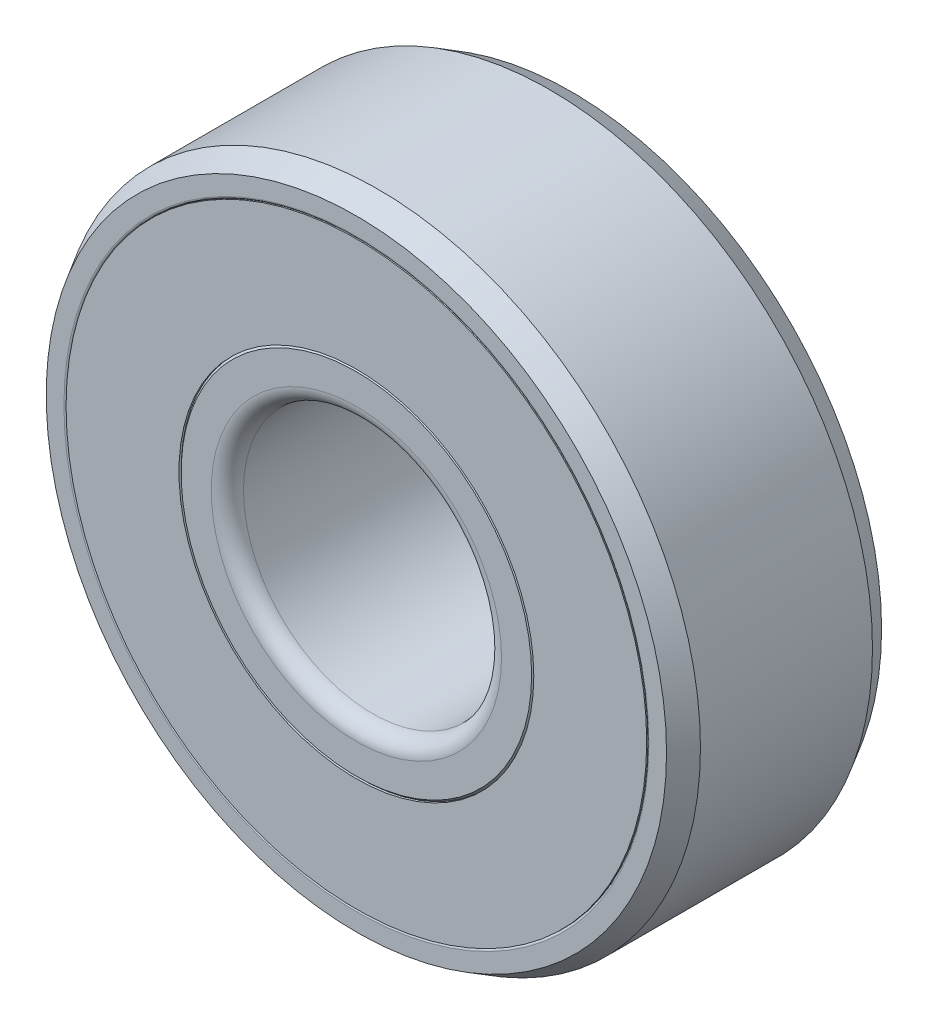
SolidWorks part; units mm, degrees
ref_plane "Front Plane" through (0, 0, 0) normal (0, 0, 1) x (1, 0, 0)
ref_plane "Top Plane" through (0, 0, 0) normal (0, 1, 0) x (1, 0, 0)
ref_plane "Right Plane" through (0, 0, 0) normal (1, 0, 0) x (0, 0, -1)
sketch "Sketch1" plane through (0, 0, 0) normal (0, 0, 1) x (1, 0, 0)
  line L0 (0, 5.25) -> (0, 7.5) construction
  line L1 (0, 3) -> (0, 5.25) construction
  line L2 (0, 7.5) -> (0, 6.75) construction
  line L3 (0, 6.75) -> (0, 6) construction
  line L4 (0, 6) -> (0, 5.25) construction
  circle A0 centre (0, 0) radius 3
  circle A1 centre (0, 0) radius 7.5
  circle A2 centre (0, 0) radius 6.75 construction
  circle A4 centre (0, 0) radius 4.125 construction
  point P6 (0, 4.125)
  dimension "OD" = 15
  dimension "ID" = 6
sketch "Sketch2" plane through (0, 0, 0) normal (1, 0, 0) x (0, 0, -1)
  line L0 (-2.5, 7.5) -> (2.5, 7.5) construction
  line L1 (2.5, 7.5) -> (2.5, -7.5) construction
  line L2 (2.5, 0) -> (-2.5, 0) construction
  line L3 (-2.5, 3) -> (-2.5, -3) construction
  point P2 (0, 7.5)
  dimension "Width" = 5
  dimension "For Shaft Diameter" = 6
  dimension "For Housing ID" = 15
sketch "Sketch3" plane through (0, 0, 0) normal (1, 0, 0) x (0, 0, -1)
  line L0 (-2, -7.5) -> (2, -7.5)
  line L3 (-2.5, -6.8) -> (-2.5, -7.2113)
  line L4 (0, -4.125) -> (0, -6.75) construction
  line L5 (-2, -7.5) -> (-2.5, -7.2113)
  line L6 (-2.125, -3) -> (2.125, -3)
  line L7 (-1.25, -6.75) -> (-1.25, -7) construction
  line L8 (-2.45, -4.125) -> (-1.25, -4.125)
  line L9 (-2.5, -4.125) -> (0, -4.125) construction
  line L11 (-2.5, -6.75) -> (-2.5, -4.125) construction
  line L12 (-2.5, -4.075) -> (-2.5, -3.375)
  line L14 (-2.5, 0) -> (2.5, 0) construction
  line L15 (-2.45, -6.75) -> (-1.25, -6.75)
  line L17 (0, 0) -> (0, -7.5) construction
  line L18 (-1.25, -7) -> (-1.25, -7.25) construction
  line L19 (2, -7.5) -> (2.5, -7.2113)
  line L20 (0, -6.75) -> (-2.5, -6.75) construction
  line L21 (-2.5, 3) -> (-2.5, -3) construction
  line L22 (-1.25, -7.25) -> (-1.25, -7.5) construction
  line L30 (-2.5, -4.075) -> (-2.45, -4.125)
  line L31 (2.45, -4.125) -> (1.25, -4.125)
  line L32 (2.5, -4.075) -> (2.45, -4.125)
  line L33 (2.5, -4.075) -> (2.5, -3.375)
  line L34 (2.45, -6.75) -> (1.25, -6.75)
  line L35 (2.5, -6.8) -> (2.5, -7.2113)
  line L36 (0, 7.5) -> (0, -7.5) construction
  arc A0 (0, -3.625) -> (0, -7.25) centre (0, -5.4375) ccw construction
  arc A1 (-1.25, -4.125) -> (1.25, -4.125) centre (0, -5.4375) cw
  arc A2 (-1.25, -6.75) -> (1.25, -6.75) centre (0, -5.4375) ccw
  arc A4 (-2.45, -6.75) -> (-2.5, -6.8) centre (-2.45, -6.8) ccw
  arc A5 (-2.125, -3) -> (-2.5, -3.375) centre (-2.125, -3.375) ccw
  arc A6 (2.125, -3) -> (2.5, -3.375) centre (2.125, -3.375) cw
  arc A7 (2.45, -6.75) -> (2.5, -6.8) centre (2.45, -6.8) cw
  point P28 (0, -5.4375)
  point P46 (-2.5, -3)
  point P54 (0, -3)
  dimension "D4" = 0.05
  dimension "D7" = 0.375
  dimension "D5" = 45
  dimension "D6" = 0.05
  dimension "D3" = 0.5
  dimension "D2" = 60
revolve "Revolve1" add sketch "Sketch3" angle 360 about L14
sketch "Sketch4" plane through (0, 0, 0) normal (1, 0, 0) x (0, 0, -1)
  line L0 (-2.45, -6.75) -> (-1.25, -6.75) construction
  line L1 (-2.5, -4.125) -> (-1.9844, -4.125)
  line L2 (-2.5, -4.125) -> (-2.5, -6.75)
  line L3 (-2.5, -6.75) -> (-1.9844, -6.75)
  line L4 (-1.9844, -4.125) -> (-1.9844, -6.75)
  line L5 (-2.5, -4.075) -> (-2.5, -3.375) construction
  line L6 (-2.5, -5.4375) -> (-2.3281, -5.4375) construction
  line L7 (-2.3281, -5.4375) -> (-2.1562, -5.4375) construction
  line L8 (-2.1562, -5.4375) -> (-1.9844, -5.4375) construction
  line L9 (-1.9844, -5.4375) -> (-1.8125, -5.4375) construction
  line L10 (-2.5, -6.75) -> (-2.5, -4.125) construction
  line L11 (-2.45, -4.125) -> (-1.25, -4.125) construction
  arc A1 (0, -3.625) -> (0, -7.25) centre (0, -5.4375) ccw construction
revolve "Revolve2" add sketch "Sketch4" angle 360 about L14
sketch "Sketch5" plane through (0, 0, 0) normal (1, 0, 0) x (0, 0, -1)
  line L2 (0, -3.625) -> (0, -7.25)
  arc A2 (0, -7.25) -> (0, -3.625) centre (0, -5.4375) cw
revolve "Revolve3" add sketch "Sketch5" angle 360 about L17
pattern_circular "CirPattern1" count 7 over 360 about axis through (0, 0, 0) along (0, 0, 1) of bodies 138
equation "\"D4@Sketch3\"=\"Width@Sketch2\"*.01"
equation "\"D6@Sketch3\"=\"Width@Sketch2\"*.01"
equation "\"D7@Sketch3\"=\"Width@Sketch2\"*.075"
equation "\"D3@Sketch3\"=\"Width@Sketch2\"*.1"
